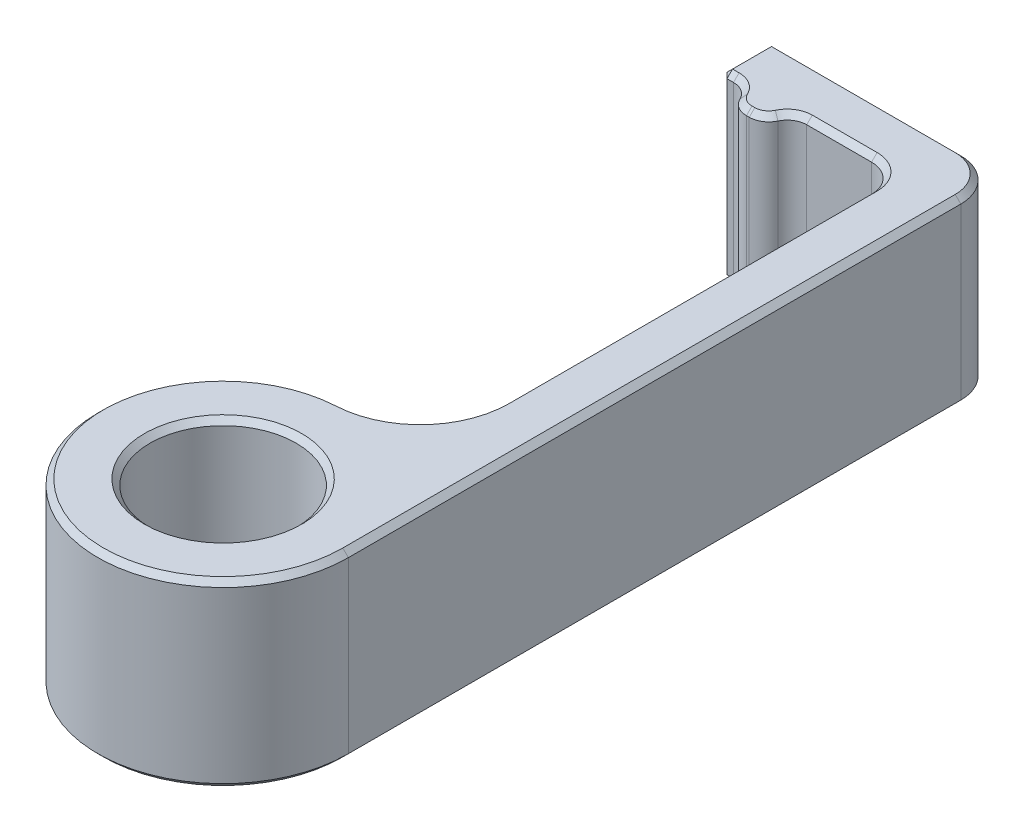
SolidWorks part; units mm, degrees
ref_plane "前视基准面" through (0, 0, 0) normal (0, 0, 1) x (1, 0, 0)
ref_plane "上视基准面" through (0, 0, 0) normal (0, 1, 0) x (1, 0, 0)
ref_plane "右视基准面" through (0, 0, 0) normal (1, 0, 0) x (0, 0, -1)
other "Configuration Table"
sketch "草图1" plane through (0, 0, 0) normal (0, 1, 0) x (1, 0, 0)
  line L0 (5.1882, 7.3541) -> (5.1882, 43.4)
  line L2 (9, 0) -> (9, 47)
  line L3 (9, 47) -> (5.4, 47)
  line L5 (5.4, 47) -> (-7.6, 47)
  line L7 (5.1882, 43.4) -> (-7.6, 43.4)
  line L8 (-7.6, 47) -> (-7.6, 43.4)
  circle A0 centre (0, 0) radius 5.25
  arc A1 (5.1882, 7.3541) -> (9, 0) centre (0, 0) ccw
  dimension "D1" = 10.5
  dimension "D2" = 18
  dimension "D3" = 3.6
  dimension "D4" = 47
  dimension "D5" = 13
  dimension "D6" = 3.6
extrude "凸台-拉伸1" add sketch "草图1" along normal blind 13
fillet "圆角1" radius 6 1 edges at (5.1882, 6.5, -7.3541)
fillet "圆角2" radius 2 1 edges at (5.1882, 6.5, -43.4)
fillet "圆角3" radius 3 1 edges at (9, 6.5, -47)
sketch "草图2" plane through (0, 0, -43.4) normal (0, 0, 1) x (1, 0, 0)
  line L0 (-7.6, 13) -> (3.1882, 13) construction
  line L1 (-5.6, 13) -> (-2.6, 13)
  line L2 (-5.6, 13) -> (-5.6, 0)
  line L3 (-5.6, 0) -> (-2.6, 0)
  line L4 (-2.6, 13) -> (-2.6, 0)
  line L5 (-7.6, 0) -> (3.1882, 0) construction
  line L6 (-7.6, 13) -> (-7.6, 0) construction
  dimension "D1" = 2
  dimension "D2" = 3
extrude "凸台-拉伸2" add sketch "草图2" along normal blind 1.6
fillet "圆角4" radius 1.4 2 edges at (-2.6, 6.5, -41.8) (-5.6, 6.5, -41.8)
fillet "圆角5" radius 1.4 2 edges at (-2.6, 6.5, -43.4) (-5.6, 6.5, -43.4)
chamfer "倒角1" distance 0.4 angle 45 34 edges at (0, 0, 5.25) (-7.6, 0, -45.2) (0.859, 0, -43.4) (-7.1649, 0, -43.4) (4.6024, 0, -42.8142) (5.1882, 0, -28.189) (3.5442, 0, -10.8518) (-6.1894, 0, 6.5339) (9, 0, -22) (8.1213, 0, -46.1213) (-0.8, 0, -47) (0, 13, 5.25) (-6.1894, 13, 6.5339) (3.5442, 13, -10.8518) (5.1882, 13, -28.189) (4.6024, 13, -42.8142) (0.859, 13, -43.4) (-7.1649, 13, -43.4) (-7.6, 13, -45.2) (-0.8, 13, -47) (8.1213, 13, -46.1213) (9, 13, -22) (-7.6, 6.5, -47) (-7.6, 6.5, -43.4) (-2.2185, 0, -43.1832) (-3.2517, 0, -42.0168) (-4.1, 0, -41.8) (-4.9483, 0, -42.0168) (-5.9815, 0, -43.1832) (-4.9483, 13, -42.0168) (-5.9815, 13, -43.1832) (-2.2185, 13, -43.1832) (-3.2517, 13, -42.0168) (-4.1, 13, -41.8)
